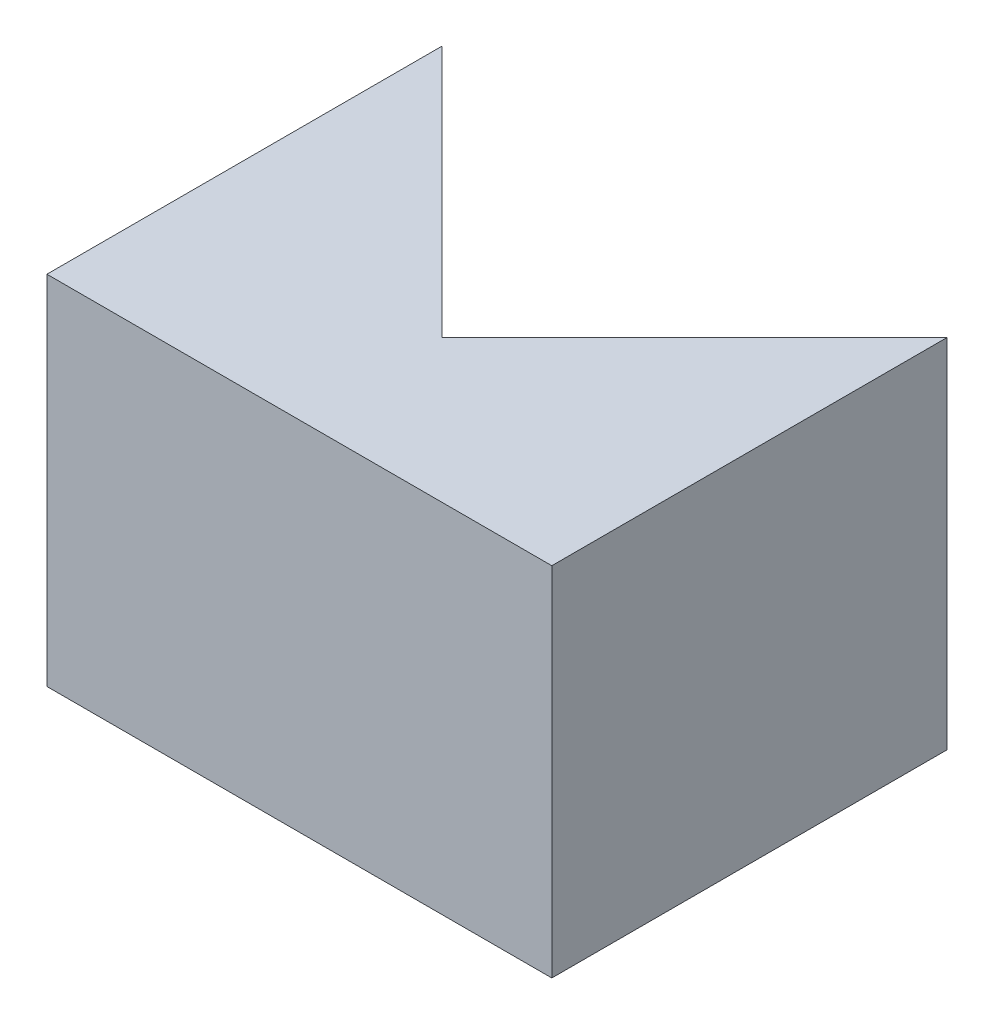
SolidWorks part; units mm, degrees
ref_plane "Front Plane" through (0, 0, 0) normal (0, 0, 1) x (1, 0, 0)
ref_plane "Top Plane" through (0, 0, 0) normal (0, 1, 0) x (1, 0, 0)
ref_plane "Right Plane" through (0, 0, 0) normal (1, 0, 0) x (0, 0, -1)
sketch "Sketch1" plane through (0, 0, 0) normal (0, 0, 1) x (1, 0, 0)
  line L1 (-10.5705, 7.2135) -> (17.7095, 7.2135)
  line L2 (-10.5705, 7.2135) -> (-10.5705, -12.7865)
  line L3 (-10.5705, -12.7865) -> (17.7095, -12.7865)
  line L4 (17.7095, 7.2135) -> (17.7095, -12.7865)
  dimension "D1" = 28.28
  dimension "D2" = 20
extrude "Boss-Extrude1" add sketch "Sketch1" along normal blind 40 contours L2 L1 L4 L3
sketch "Sketch2" plane through (0, -12.7865, 0) normal (0, -1, 0) x (1, 0, 0)
  line L0 (-10.5705, 0) -> (3.5695, 14.14)
  line L1 (3.5695, 14.14) -> (17.7095, 0)
  line L2 (17.7095, 40) -> (17.7095, 0) construction
  line L3 (-10.5705, 40) -> (-10.5705, 0) construction
  line L4 (-10.5705, 22.14) -> (17.7095, 22.14)
  line L5 (17.7095, 0) -> (-10.5705, 0)
  line L6 (-10.5705, 22.14) -> (-10.5705, 40)
  line L7 (-10.5705, 40) -> (17.7095, 40) construction
  line L8 (-10.5705, 40) -> (17.7095, 40)
  line L9 (17.7095, 40) -> (17.7095, 22.14)
  dimension "D1" = 45
  dimension "D2" = 45
  dimension "D3" = 8
extrude "Cut-Extrude1" cut sketch "Sketch2" against normal blind 29 contours L9 L4 L6 L8 | L5 L0 L1
sketch "Sketch3" plane through (-5.2852, 0, 5.2852) normal (0.7071, 0, -0.7071) x (-0.7071, 0, -0.7071)
  line L0 (7.4745, -12.7865) -> (-12.5225, 7.2135) construction
  line L1 (-12.5225, 7.2135) -> (-12.5225, -12.7865) construction
  line L2 (-12.5225, 7.2135) -> (-12.5225, -12.7865) construction
  line L3 (7.4745, -12.7865) -> (-12.5225, -12.7865) construction
  line L4 (-12.5225, -12.7865) -> (7.4745, 7.2135) construction
  circle A0 centre (-2.524, -2.7865) radius 2.675
  point P13 (-2.524, -2.7865)
  dimension "D1" = 5.35
extrude "Cut-Extrude2" cut sketch "Sketch3" against normal blind 19
sketch "Sketch4" plane through (-5.2852, 0, 5.2852) normal (0.7071, 0, -0.7071) x (-0.7071, 0, -0.7071)
  circle A0 centre (-2.524, -2.7865) radius 5
  dimension "D1" = 10
extrude "Cut-Extrude3" cut sketch "Sketch4" against normal blind 19 from offset 7 offset against normal yes
sketch3d "3DSketch1" plane through (0, 0, 0) normal (0, 0, 1) x (1, 0, 0)
  dimension "D1" = 14.14
